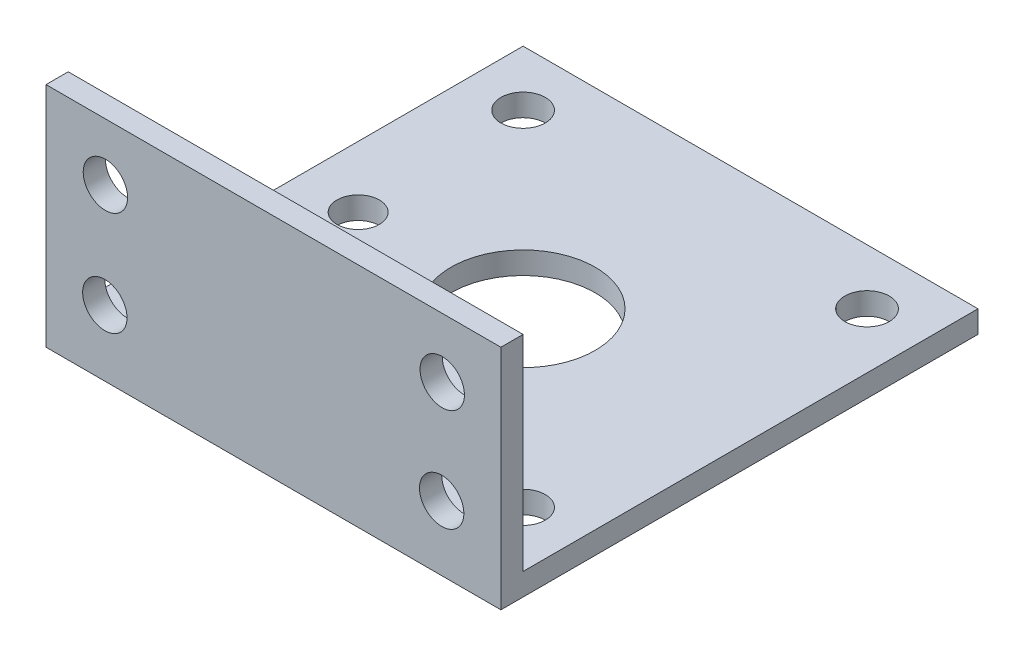
SolidWorks part; units mm, degrees
ref_plane "Front Plane" through (0, 0, 0) normal (0, 0, 1) x (1, 0, 0)
ref_plane "Top Plane" through (0, 0, 0) normal (0, 1, 0) x (1, 0, 0)
ref_plane "Right Plane" through (0, 0, 0) normal (1, 0, 0) x (0, 0, -1)
sketch "Sketch1" plane through (0, 0, 0) normal (0, 1, 0) x (1, 0, 0)
  line L0 (0, 0) -> (0, 20.5) construction
  line L1 (-20.5, 20.5) -> (20.5, 20.5)
  line L2 (-20.5, 20.5) -> (-20.5, -20.5)
  line L3 (-20.5, -20.5) -> (20.5, -20.5)
  line L4 (20.5, 20.5) -> (20.5, -20.5)
  line L5 (-20.5, 20.5) -> (20.5, -20.5) construction
  line L6 (-20.5, -20.5) -> (20.5, 20.5) construction
  line L7 (0, 0) -> (0, -20.5) construction
  line L8 (0, 0) -> (20.5, 0) construction
  line L9 (0, 0) -> (-20.5, 0) construction
  line L10 (26.906, 0) -> (26.906, 15.5)
  line L11 (15.5, 26.187) -> (15.5, -35.9588) construction
  line L12 (0, 26.187) -> (15.5, 26.187)
  line L13 (26.906, 15.5) -> (-25.856, 15.5) construction
  line L14 (48.1525, 15.5) -> (48.1525, -15.5)
  circle A0 centre (0, 0) radius 6.5
  circle A1 centre (15.5, 15.5) radius 2
  circle A2 centre (-15.5, 15.5) radius 2
  circle A3 centre (15.5, -15.5) radius 2
  circle A4 centre (-15.5, -15.5) radius 2
  point P0 (0, 0)
  dimension "D3" = 13
  dimension "D6" = 4
  dimension "D1" = 41
  dimension "D2" = 41
  dimension "D4" = 15.5
  dimension "D5" = 15.5
  dimension "D7" = 31
extrude "Boss-Extrude1" add sketch "Sketch1" along normal blind 2 contours L4 L1 L2 L3 A4 A2 A1 A0 A3
ref_plane "Plane1" through (0, 0, 20.5) normal (0, 0, 1) x (1, 0, 0)
sketch "Sketch2" plane through (0, 0, 20.5) normal (0, 0, 1) x (1, 0, 0)
  line L0 (-20.5, 2) -> (-20.5, 0) construction
  line L5 (-20.5, 0) -> (20.5, 0)
  line L6 (-20.5, 0) -> (-20.5, 20.5)
  line L7 (-20.5, 20.5) -> (20.5, 20.5)
  line L8 (20.5, 0) -> (20.5, 20.5)
  line L9 (0, 0) -> (0, 41) construction
  line L10 (-20.5, 10.25) -> (20.5, 10.25) construction
  line L11 (24.7115, 20.5) -> (24.7115, 36)
  line L12 (0, 43.2822) -> (15.5, 43.2822)
  line L13 (15.5, 43.2822) -> (15.5, 24.5356) construction
  line L14 (24.7115, 36) -> (8.9915, 36) construction
  circle A3 centre (-15.5, -15.5) radius 2
  circle A4 centre (15.5, -15.5) radius 2
  dimension "D1" = 20.5
  dimension "D2" = 41
  dimension "D4" = 15.5
  dimension "D5" = 15.5
extrude "Boss-Extrude2" add sketch "Sketch2" along normal blind 2
sketch "Sketch3" plane through (0, 0, 20.5) normal (0, 0, -1) x (-1, 0, 0)
  line L0 (0.0307, 1.9238) -> (-0.0307, 20.438) construction
  line L1 (-11.2849, 10.5082) -> (11.4904, 10.6293)
  circle A0 centre (-15.1615, 5.8441) radius 2
  circle A1 centre (15.1965, 5.9446) radius 2
  circle A2 centre (15.1465, 15.3532) radius 2
  circle A3 centre (-15.2109, 15.1308) radius 2
  point P5 (0.1028, 10.5688)
  dimension "D1" = 4
extrude "Cut-Extrude1" cut sketch "Sketch3" against normal blind 10 contours A0 | A2 | A3 | A1
sketch "Sketch5" plane through (0, 0, 0) normal (0, -1, 0) x (1, 0, 0)
  circle A0 centre (-15.0715, -0.1789) radius 1.921
sketch "Sketch6" plane through (0, 0, 0) normal (0, -1, 0) x (-1, 0, 0)
  circle A0 centre (14.9734, 0.1056) radius 1.9114
extrude "Cut-Extrude4" cut sketch "Sketch6" against normal blind 10
